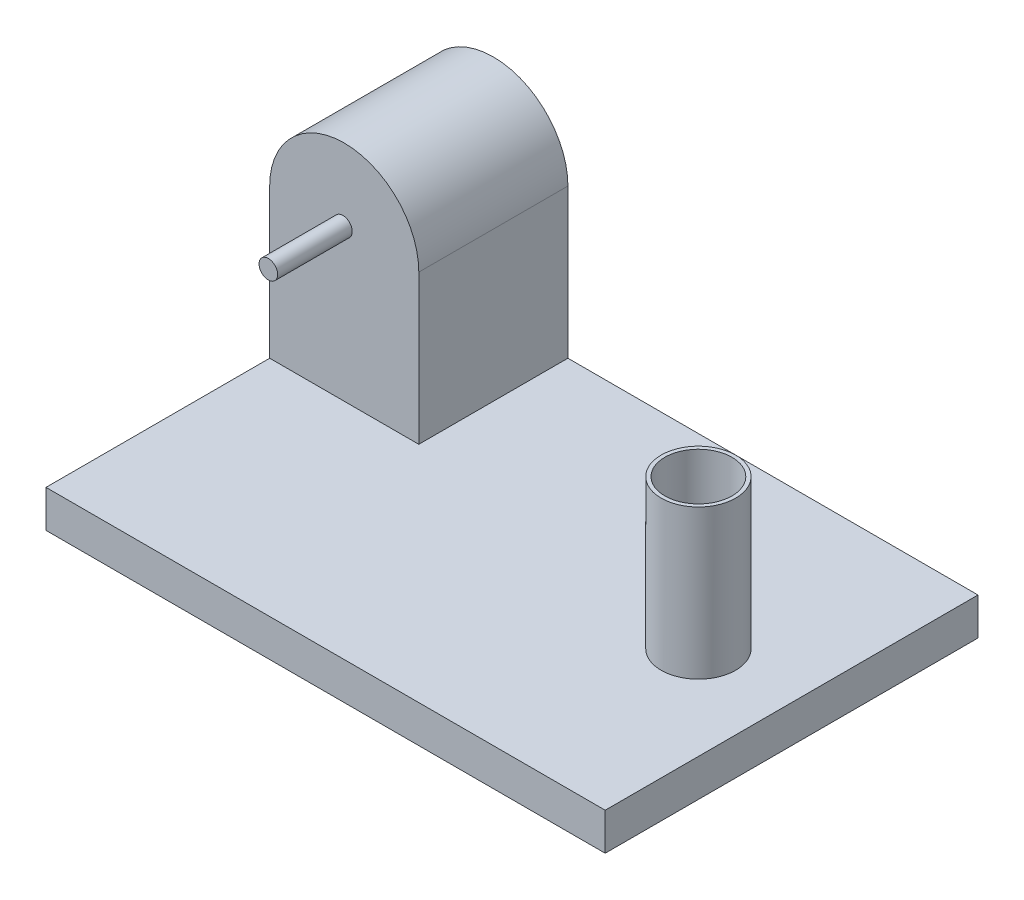
SolidWorks part; units mm, degrees
ref_plane "Front Plane" through (0, 0, 0) normal (0, 0, 1) x (1, 0, 0)
ref_plane "Top Plane" through (0, 0, 0) normal (0, 1, 0) x (1, 0, 0)
ref_plane "Right Plane" through (0, 0, 0) normal (1, 0, 0) x (0, 0, -1)
sketch "Sketch1" plane through (0, 0, 0) normal (0, 1, 0) x (1, 0, 0)
  line L1 (-75, -50) -> (75, -50)
  line L2 (-75, -50) -> (-75, 50)
  line L3 (-75, 50) -> (75, 50)
  line L4 (75, -50) -> (75, 50)
  line L5 (-75, -50) -> (75, 50) construction
  line L6 (-75, 50) -> (75, -50) construction
  point P0 (0, 0)
  dimension "D1" = 100
  dimension "D2" = 150
extrude "Boss-Extrude1" add sketch "Sketch1" along normal blind 10
sketch "Sketch2" plane through (0, 10, 0) normal (0, 1, 0) x (1, 0, 0)
  line L0 (75, -50) -> (75, 50) construction
  circle A0 centre (50, 0) radius 10
  dimension "D1" = 20
  dimension "D2" = 25
extrude "Boss-Extrude2" add sketch "Sketch2" along normal blind 40
sketch "Sketch3" plane through (0, 50, 0) normal (0, 1, 0) x (1, 0, 0)
  line L0 (75, -50) -> (75, 50) construction
  circle A0 centre (50, 0) radius 9
  dimension "D1" = 18
  dimension "D2" = 25
extrude "Cut-Extrude2" cut sketch "Sketch3" against normal blind 40
sketch "Sketch4" plane through (0, 10, 0) normal (0, 1, 0) x (1, 0, 0)
  line L1 (-75, 10) -> (-35, 10)
  line L2 (-75, 10) -> (-75, 50)
  line L3 (-75, 50) -> (-35, 50)
  line L4 (-35, 10) -> (-35, 50)
  line L5 (-75, 10) -> (-35, 50) construction
  line L6 (-75, 50) -> (-35, 10) construction
  line L7 (-75, 50) -> (-75, -50) construction
  line L8 (75, 50) -> (-75, 50) construction
  point P0 (-55, 30)
  dimension "D1" = 40
  dimension "D2" = 40
  dimension "D3" = 40
  dimension "D4" = 20
extrude "Boss-Extrude3" add sketch "Sketch4" along normal blind 60
sketch "Sketch6" plane through (0, 0, -10) normal (0, 0, 1) x (1, 0, 0)
  line L0 (-35, 70) -> (-35, 10) construction
  line L1 (-75, 70) -> (-35, 70) construction
  line L3 (-75, 50) -> (-75, 70)
  line L4 (-75, 70) -> (-55, 70)
  arc A0 (-55, 70) -> (-75, 50) centre (-55, 50) ccw
  dimension "D1" = 40
  dimension "D2" = 20
  dimension "D3" = 20
extrude "Cut-Extrude3" cut sketch "Sketch6" against normal blind 50
sketch "Sketch7" plane through (0, 0, -10) normal (0, 0, 1) x (1, 0, 0)
  line L0 (-35, 70) -> (-35, 10) construction
  line L1 (-55, 70) -> (-35, 70) construction
  line L2 (-55, 70) -> (-35, 70)
  line L3 (-35, 70) -> (-35, 50)
  arc A0 (-35, 50) -> (-55, 70) centre (-55, 50) ccw
  dimension "D1" = 40
  dimension "D2" = 20
extrude "Cut-Extrude4" cut sketch "Sketch7" against normal blind 50
sketch "Sketch8" plane through (0, 0, -10) normal (0, 0, 1) x (1, 0, 0)
  circle A0 centre (-55.3533, 50.4918) radius 2.5
  dimension "D1" = 5
extrude "Boss-Extrude5" add sketch "Sketch8" along normal blind 20
